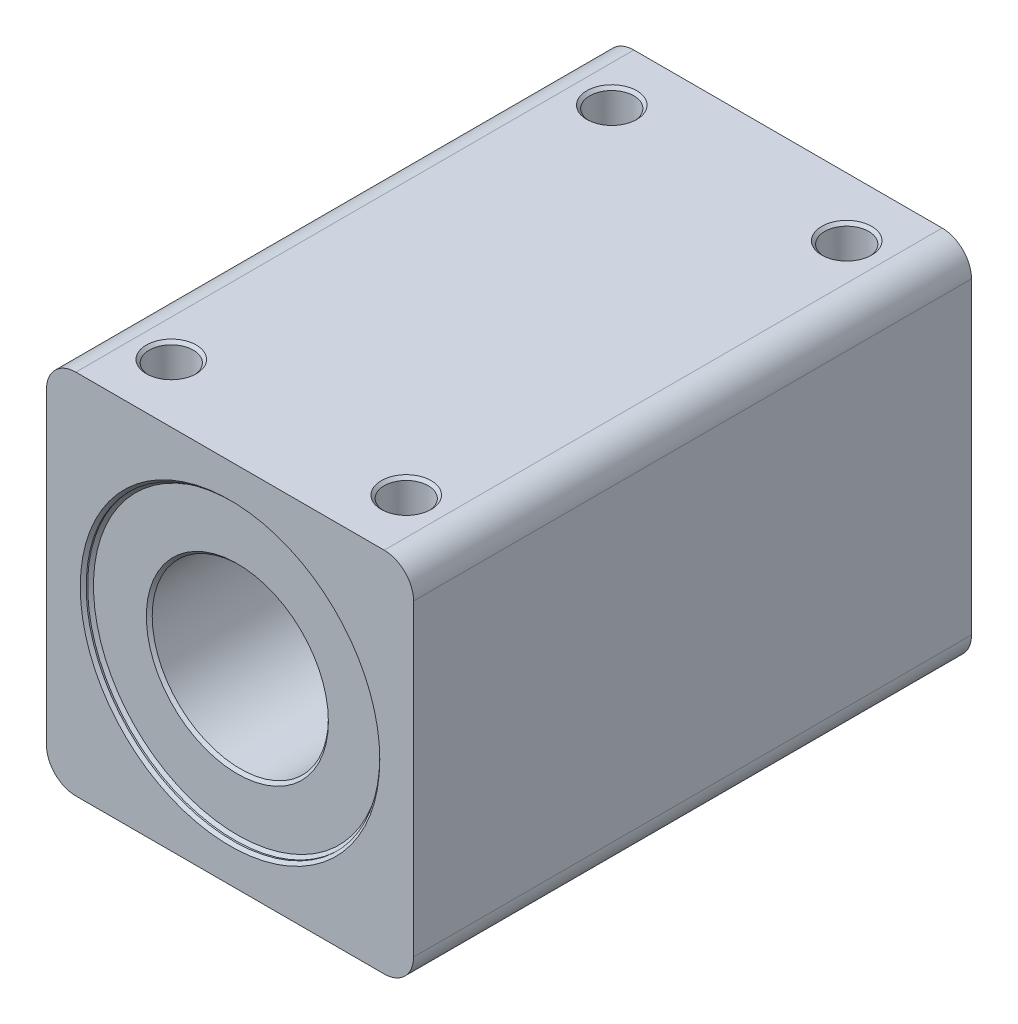
SolidWorks part; units mm, degrees
ref_plane "FRONT" through (0, 0, 0) normal (0, 0, 1) x (1, 0, 0)
ref_plane "TOP" through (0, 0, 0) normal (0, 1, 0) x (1, 0, 0)
ref_plane "RIGHT" through (0, 0, 0) normal (1, 0, 0) x (0, 0, -1)
sketch "Sketch1" plane through (0, 0, 0) normal (0, 0, 1) x (1, 0, 0)
  line L1 (-12.5, 12.5) -> (12.5, 12.5)
  line L2 (-12.5, 12.5) -> (-12.5, -12.5)
  line L3 (-12.5, -12.5) -> (12.5, -12.5)
  line L4 (12.5, 12.5) -> (12.5, -12.5)
  circle A0 centre (0, 0) radius 6
  point P4 (0, 12.5)
  point P6 (-12.5, 0)
  dimension "D2" = 12
  dimension "D1" = 25
extrude "Base-Extrude" add sketch "Sketch1" along normal mid plane 38
sketch "Sketch2" plane through (0, 0, 19) normal (0, 0, 1) x (1, 0, 0)
  circle A0 centre (0, 0) radius 10
  dimension "D1" = 20
extrude "FrontDetail" cut sketch "Sketch2" against normal blind 0.5
mirror "Mirror1" about plane through (0, 0, 0) normal (0, 0, 1) of "FrontDetail"
fillet "Fillet1" radius 2 4 edges at (-12.5, 12.5, 0) (12.5, 12.5, 0) (12.5, -12.5, 0) (-12.5, -12.5, 0)
sketch "Sketch3" plane through (0, 12.5, 0) normal (0, 1, 0) x (-1, 0, 0)
  line L0 (-10.5, 19) -> (10.5, 19) construction
  line L1 (0, 0) -> (0, 22.0673) construction
  line L2 (0, 18.5) -> (0, -18.5) construction
  circle A0 centre (-8, 15) radius 1.5
  circle A1 centre (8, 15) radius 1.5
  circle A2 centre (-8, -15) radius 1.5
  circle A3 centre (8, -15) radius 1.5
  dimension "D1" = 3
  dimension "D2" = 4
  dimension "D3" = 30
  dimension "D4" = 16
extrude "Mounts" cut sketch "Sketch3" against normal blind 4.5
chamfer "Chamfer1" distance 0.2 angle 45 10 edges at (10, 0, 18.5) (6, 0, 18.5) (10, 0, 19) (10, 0, -19) (-6, 0, -18.5) (10, 0, -18.5) (8, 12.5, 16.5) (-8, 12.5, 16.5) (8, 12.5, -13.5) (-8, 12.5, -13.5)
